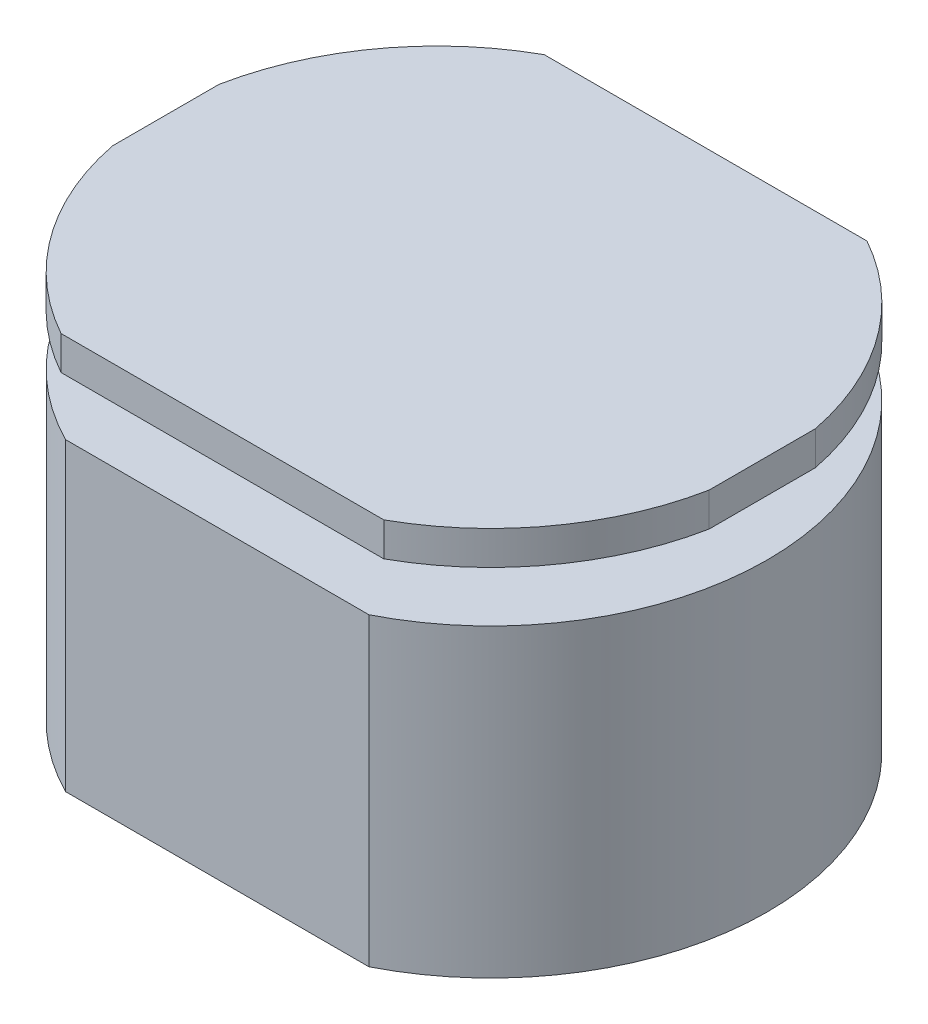
SolidWorks part; units mm, degrees
ref_plane "Plano frontal" through (0, 0, 0) normal (0, 0, 1) x (1, 0, 0)
ref_plane "Plano superior" through (0, 0, 0) normal (0, 1, 0) x (1, 0, 0)
ref_plane "Plano direito" through (0, 0, 0) normal (1, 0, 0) x (0, 0, -1)
sketch "Esboço1" plane through (0, 0, 0) normal (0, 1, 0) x (1, 0, 0)
  line L1 (294.5, -239.5) -> (-294.5, -239.5)
  line L2 (294.5, -239.5) -> (294.5, 239.5)
  line L3 (294.5, 239.5) -> (-294.5, 239.5)
  line L4 (-294.5, -239.5) -> (-294.5, 239.5)
  line L5 (294.5, -239.5) -> (-294.5, 239.5) construction
  line L6 (294.5, 239.5) -> (-294.5, -239.5) construction
  point P0 (0, 0)
  dimension "D1" = 589
  dimension "D2" = 479
extrude "Ressalto-extrusão1" add sketch "Esboço1" along normal blind 296
sketch "Esboço2" plane through (0, 296, 0) normal (0, 1, 0) x (1, 0, 0)
  line L1 (-110, 90) -> (110, 90)
  line L2 (-110, 90) -> (-110, -90)
  line L3 (-110, -90) -> (110, -90)
  line L4 (110, 90) -> (110, -90)
  line L5 (-110, 90) -> (110, -90) construction
  line L6 (-110, -90) -> (110, 90) construction
  point P0 (0, 0)
  dimension "D1" = 220
  dimension "D2" = 180
extrude "Ressalto-extrusão2" add sketch "Esboço2" along normal blind 49.2
sketch "Esboço3" plane through (0, 345.2, 0) normal (0, 1, 0) x (1, 0, 0)
  line L1 (-289.5, 234.5) -> (289.5, 234.5)
  line L2 (-289.5, 234.5) -> (-289.5, -234.5)
  line L3 (-289.5, -234.5) -> (289.5, -234.5)
  line L4 (289.5, 234.5) -> (289.5, -234.5)
  line L5 (-289.5, 234.5) -> (289.5, -234.5) construction
  line L6 (-289.5, -234.5) -> (289.5, 234.5) construction
  point P0 (0, 0)
  dimension "D1" = 579
  dimension "D2" = 469
extrude "Ressalto-extrusão3" add sketch "Esboço3" along normal blind 32.8
sketch "Esboço4" plane through (0, 378, 0) normal (0, 1, 0) x (1, 0, 0)
  line L0 (0, 239.5) -> (0, -239.5) construction
  line L1 (294.5, 239.5) -> (-294.5, 239.5) construction
  line L3 (147.25, 239.5) -> (-147.25, 239.5) construction
  line L4 (-294.5, -239.5) -> (294.5, -239.5) construction
  line L5 (-147.25, -239.5) -> (147.25, -239.5) construction
  line L6 (-294.5, 239.5) -> (-294.5, -239.5) construction
  line L8 (-147.25, 239.5) -> (-294.5, 239.5)
  line L9 (-294.5, 239.5) -> (-294.5, -239.5)
  line L10 (-294.5, -239.5) -> (-147.25, -239.5)
  line L11 (147.25, -239.5) -> (294.5, -239.5)
  line L12 (294.5, -239.5) -> (294.5, 239.5)
  line L13 (294.5, 239.5) -> (147.25, 239.5)
  arc A0 (-147.25, 239.5) -> (-147.25, -239.5) centre (-26.1034, 0) ccw
  arc A1 (147.25, 239.5) -> (147.25, -239.5) centre (26.1034, 0) cw
  arc A2 (147.25, 239.5) -> (147.25, -239.5) centre (26.1034, 0) cw
  point P14 (-294.5, 0)
  line M3 (289.5, -234.5) -> (289.5, 234.5)
  line M4 (289.5, 234.5) -> (-289.5, 234.5)
  line M5 (-289.5, 234.5) -> (-289.5, -234.5)
  line M6 (-289.5, -234.5) -> (289.5, -234.5)
  dimension "D1" = 147.25
extrude "Corte-extrusão1" cut sketch "Esboço4" against normal up to surface (378 mm away) contours A0 M5 M6 | A0 M4 M5 | A1 M4 M3 | A1 M3 M6 | L13 A1 L12 M4 M3 | L12 A1 L11 M3 M6 | A0 L9 L10 M6 M5 | A0 L8 L9 M5 M4 up to face at (0, 0, 0)
